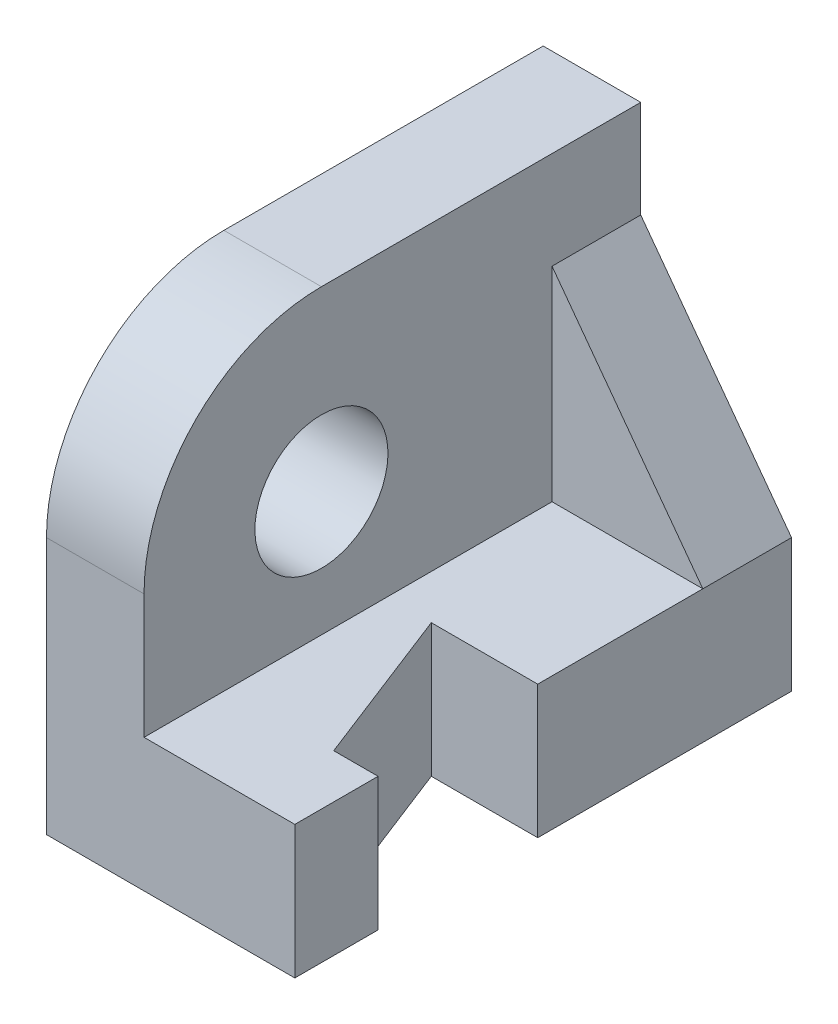
SolidWorks part; units mm, degrees
ref_plane "Ön Düzlem" through (0, 0, 0) normal (0, 0, 1) x (1, 0, 0)
ref_plane "Üst Düzlem" through (0, 0, 0) normal (0, 1, 0) x (1, 0, 0)
ref_plane "Sağ Düzlem" through (0, 0, 0) normal (1, 0, 0) x (0, 0, -1)
sketch "Çizim1" plane through (0, 0, 0) normal (0, 0, 1) x (1, 0, 0)
  line L1 (-62.0149, 24.699) -> (-51.0149, 24.699)
  line L2 (-62.0149, 24.699) -> (-62.0149, -24.301)
  line L3 (-62.0149, -24.301) -> (-51.0149, -24.301)
  line L4 (-51.0149, 24.699) -> (-51.0149, -9.301)
  line L5 (-51.0149, -24.301) -> (-34.0149, -24.301)
  line L7 (-51.0149, -9.301) -> (-34.0149, -9.301)
  line L8 (-34.0149, -24.301) -> (-34.0149, -9.301)
  dimension "D1" = 11
  dimension "D2" = 15
  dimension "D3" = 49
  dimension "D4" = 28
extrude "Yükseklik-Ekstrüzyon1" add sketch "Çizim1" along normal blind 56
fillet "Radyus1" radius 20 1 edges at (-56.5149, 24.699, 56)
sketch "Çizim2" plane through (-51.0149, 0, 0) normal (1, 0, 0) x (0, 0, -1)
  circle A0 centre (-36, 4.699) radius 7.5
  dimension "D1" = 15
extrude "Kes-Ekstrüzyon1" cut sketch "Çizim2" against normal up to next
sketch "Çizim3" plane through (0, -9.301, 0) normal (0, 1, 0) x (1, 0, 0)
  line L0 (-34.0149, -28.6133) -> (-46.0149, -28.6133)
  line L1 (-34.0149, -56) -> (-34.0149, 0) construction
  line L2 (-46.0149, -28.6133) -> (-39.0149, -46.6133)
  line L3 (-39.0149, -46.6133) -> (-34.0149, -46.6133)
  dimension "D1" = 18
  dimension "D2" = 12
  dimension "D3" = 5
extrude "Kes-Ekstrüzyon2" cut sketch "Çizim3" against normal through all and the other way through all
ref_plane "Düzlem1" through (0, 0, 0) normal (0, 0, -1) x (-1, 0, 0)
sketch "Çizim4" plane through (0, 0, 0) normal (0, 0, -1) x (-1, 0, 0)
  line L0 (34.0149, -9.301) -> (51.0149, 13.699)
  line L1 (51.0149, -9.301) -> (51.0149, 24.699) construction
  line L2 (51.0149, 24.699) -> (62.0149, 24.699) construction
  dimension "D1" = 11
rib "Feder1" sketch "Çizim4" sketch "Çizim4" thickness 10 extrusion direction parallel to sketch draft on no parameters "D1"=10
